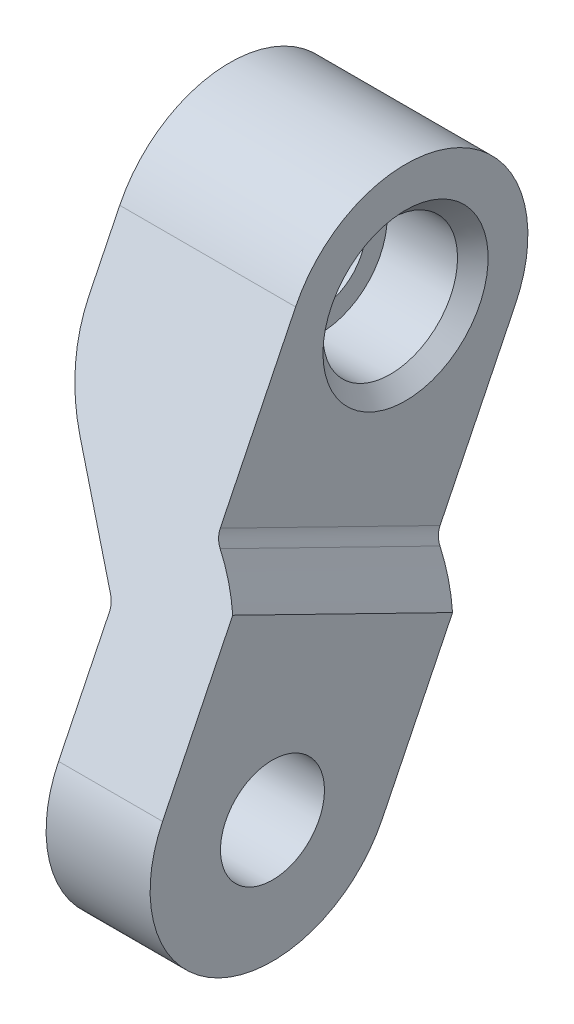
SolidWorks part; units mm, degrees
ref_plane "Front Plane" through (0, 0, 0) normal (0, 0, 1) x (1, 0, 0)
ref_plane "Top Plane" through (0, 0, 0) normal (0, 1, 0) x (1, 0, 0)
ref_plane "Right Plane" through (0, 0, 0) normal (1, 0, 0) x (0, 0, -1)
ref_plane "Plane1" through (-30.4464, 0, 0) normal (1, 0, 0) x (0, 0, -1)
sketch "Sketch1" plane through (-30.4464, 0, 0) normal (1, 0, 0) x (0, 0, -1)
  line L0 (93.907, -40.9828) -> (88.407, -52.2238)
  line L1 (95.593, -55.7398) -> (101.093, -44.4988)
  arc A0 (88.407, -52.2238) -> (95.593, -55.7398) centre (92, -53.9818) ccw
  arc A1 (101.093, -44.4988) -> (93.907, -40.9828) centre (97.5, -42.7408) ccw
extrude "Boss-Extrude1" add sketch "Sketch1" against normal blind 6.9
sketch "Sketch2" plane through (0, -48.5039, -99.1334) normal (0, -0.4395, -0.8982) x (-1, 0, 0)
  line L0 (37.3464, 0.4588) -> (33.8464, -4.0556)
  line L1 (33.8464, -4.0556) -> (33.8464, -14.2377)
  line L2 (33.8464, -14.2377) -> (37.3464, -14.2377)
  line L3 (37.3464, -14.2377) -> (37.3464, 0.4588)
extrude "Cut-Extrude1" cut sketch "Sketch2" against normal through all
sketch "Sketch3" plane through (0, -48.5039, -99.1334) normal (0, -0.4395, -0.8982) x (-1, 0, 0)
  line L0 (29.8449, 8.581) -> (29.8449, -5.2137)
  line L1 (31.5964, -1.4127) -> (31.5964, 8.581)
  line L2 (31.5964, 8.581) -> (29.8449, 8.581)
  arc A0 (29.8449, -5.2137) -> (31.5964, -1.4127) centre (34.8449, -5.2137) cw
extrude "Cut-Extrude2" cut sketch "Sketch3" against normal through all
hole_wizard "Hole1" positions "Sketch5" profile "Sketch4" legacy end condition up to next
sketch "Sketch5" plane through (-30.4464, 0, 0) normal (1, 0, 0) x (0, 0, -1)
  point P0 (92, -53.9818)
sketch "Sketch4" plane through (-30.4464, -53.9818, -92) normal (0, 1, 0) x (0, 0, -1)
  line L0 (0, 0) -> (0, 3.4)
  line L1 (0, 3.4) -> (1.7, 3.4)
  line L2 (1.7, 3.4) -> (1.7, 0)
  line L3 (1.7, 0) -> (0, 0)
  line L4 (0, 110) -> (0, -10) construction
  dimension "Diameter" = 3.4
  dimension "Depth" = 3.4
hole_wizard "Hole2" positions "Sketch7" profile "Sketch6" legacy
sketch "Sketch7" plane through (-31.5964, 0, 0) normal (1, 0, 0) x (0, 0, -1)
  point P0 (97.5, -42.7408)
sketch "Sketch6" plane through (-31.5964, -42.7408, -97.5) normal (0, 1, 0) x (0, 0, -1)
  line L0 (0, 0) -> (0, 5.75)
  line L1 (0, 5.75) -> (1.5, 5.75)
  line L2 (1.5, 5.75) -> (1.5, 2.8)
  line L3 (1.5, 2.8) -> (2.2, 2.8)
  line L4 (2.2, 2.8) -> (2.2, 0)
  line L5 (2.2, 0) -> (0, 0)
  line L6 (0, 110) -> (0, -10) construction
  dimension "Diameter" = 3
  dimension "Depth" = 5.75
  dimension "C-Bore Diameter" = 4.4
  dimension "C-Bore Depth" = 2.8
fillet "Fillet1" radius 0.6 2 edges at (-31.5964, -48.0149, -94.9195) (-33.8464, -50.3888, -93.758)
fillet "Fillet2" radius 5 1 edges at (-37.3464, -46.3338, -95.742)
chamfer "Chamfer2" distance 0.5 angle 45 1 edges at (-31.5964, -42.7408, -99.7)
